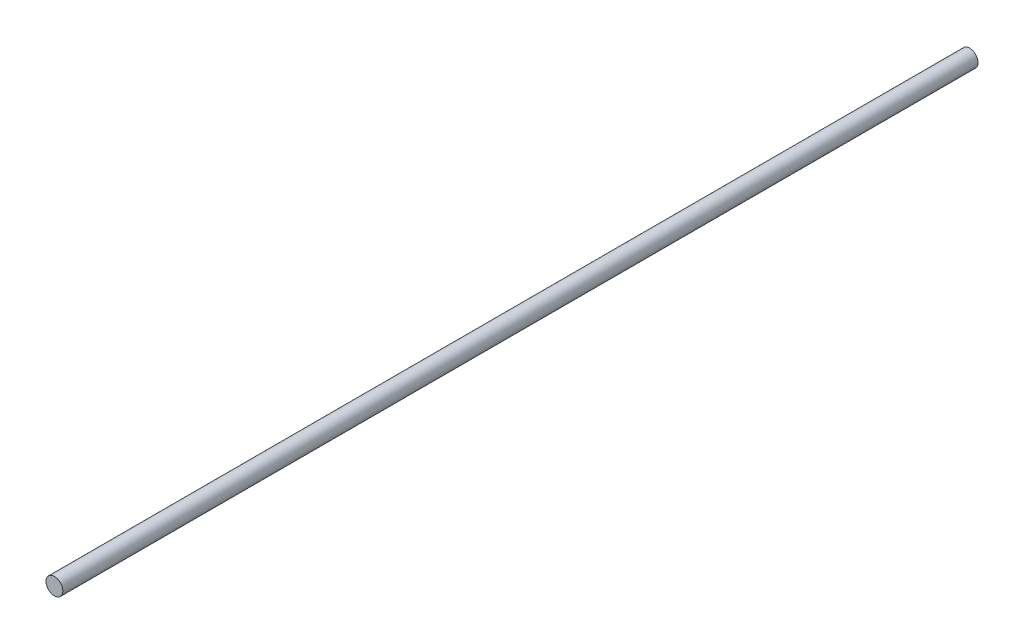
SolidWorks part; units mm, degrees
ref_plane "Alzado" through (0, 0, 0) normal (0, 0, 1) x (1, 0, 0)
ref_plane "Planta" through (0, 0, 0) normal (0, 1, 0) x (1, 0, 0)
ref_plane "Vista lateral" through (0, 0, 0) normal (1, 0, 0) x (0, 0, -1)
sketch "Croquis1" plane through (0, 0, 0) normal (0, 0, 1) x (1, 0, 0)
  circle A0 centre (0, 0) radius 4
  dimension "D1" = 8
extrude "Saliente-Extruir1" add sketch "Croquis1" along normal blind 435
